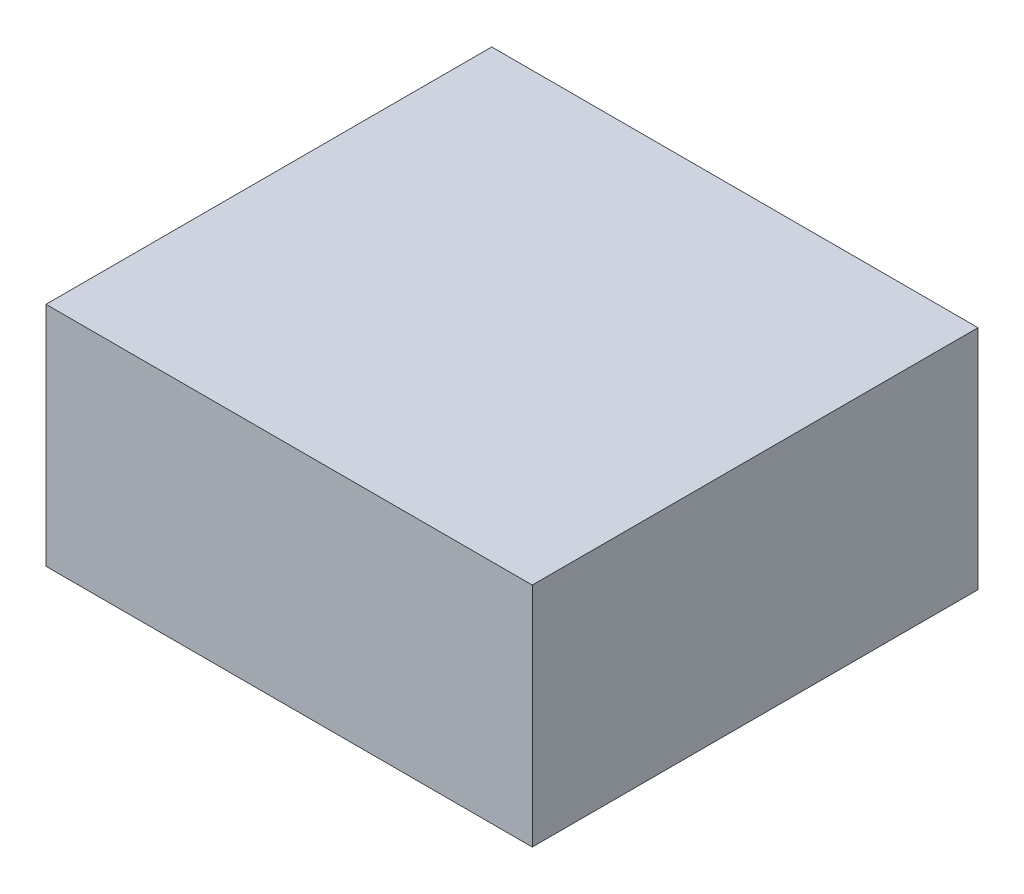
SolidWorks part; units mm, degrees
ref_plane "前视基准面" through (0, 0, 0) normal (0, 0, 1) x (1, 0, 0)
ref_plane "上视基准面" through (0, 0, 0) normal (0, 1, 0) x (1, 0, 0)
ref_plane "右视基准面" through (0, 0, 0) normal (1, 0, 0) x (0, 0, -1)
sketch "草图1" plane through (0, 0, 0) normal (0, 1, 0) x (1, 0, 0)
  line L1 (-60, 55) -> (60, 55)
  line L2 (-60, 55) -> (-60, -55)
  line L3 (-60, -55) -> (60, -55)
  line L4 (60, 55) -> (60, -55)
  line L5 (-60, 55) -> (60, -55) construction
  line L6 (-60, -55) -> (60, 55) construction
  point P0 (0, 0)
  dimension "D1" = 110
  dimension "D2" = 120
extrude "凸台-拉伸1" add sketch "草图1" along normal blind 56
